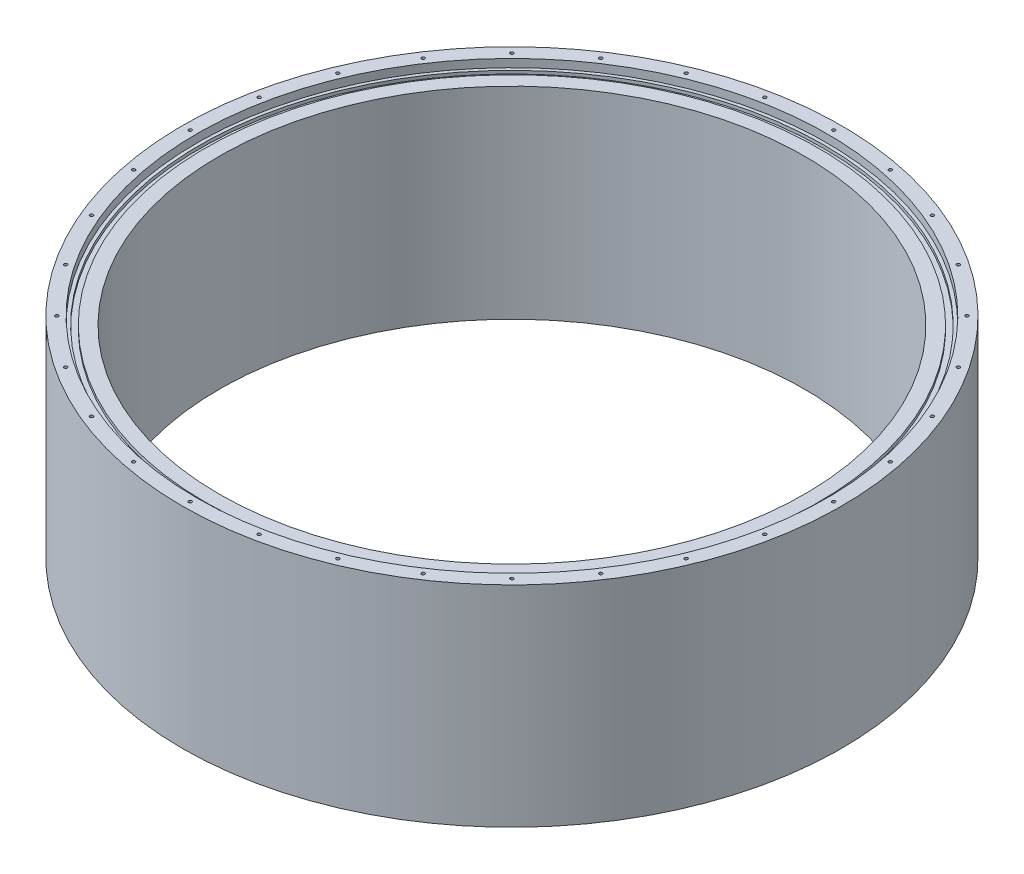
SolidWorks part; units mm, degrees
material "PVC Rigid"
ref_plane "Front" through (0, 0, 0) normal (0, 0, 1) x (1, 0, 0)
ref_plane "Top" through (0, 0, 0) normal (0, 1, 0) x (1, 0, 0)
ref_plane "Right" through (0, 0, 0) normal (1, 0, 0) x (0, 0, -1)
sketch "Sketch1" plane through (0, 0, 0) normal (0, 0, 1) x (1, 0, 0)
  line L0 (225.6, 74.685) -> (243, 74.685)
  line L1 (243, 74.685) -> (243, 80.885)
  line L2 (243, 80.885) -> (254, 80.885)
  line L3 (254, 80.885) -> (254, -80.885)
  line L4 (254, -80.885) -> (225.6, -80.885)
  line L5 (225.6, -80.885) -> (225.6, 74.685)
  line L6 (0, 80.885) -> (0, -80.885) construction
  line L7 (0, 0) -> (225.6, 0) construction
  dimension "D1" = 508
  dimension "D2" = 11
  dimension "D3" = 28.4
  dimension "D4" = 6.2
  dimension "D5" = 161.77
  dimension "D6" = 225.6
  dimension "D7" = 155.57
revolve "Revolve1" add sketch "Sketch1" angle 360 about L6
sketch "Sketch2" plane through (0, 0, 0) normal (0, 0, 1) x (1, 0, 0)
  line L0 (0, 80.885) -> (0, -80.885) construction
  line L1 (254, 80.885) -> (-254, 80.885) construction
  line L2 (-254, -80.885) -> (254, -80.885) construction
  line L3 (240.5, 72.272) -> (240.5, -77.587) construction
  line L4 (236.3344, 74.685) -> (240.5, 74.685)
  line L5 (236.3344, 74.685) -> (236.3344, 72.272)
  line L6 (236.3344, 72.272) -> (240.5, 72.272)
  line L7 (240.5, 74.685) -> (240.5, 72.272)
  line L8 (225.6, 74.685) -> (-225.6, 74.685) construction
  line L9 (225.6, 74.685) -> (-225.6, 74.685) construction
  line L10 (254, -80.885) -> (254, 80.885) construction
  line L12 (236.3344, -78.472) -> (240.5, -78.472) construction
  line L13 (236.3344, -78.472) -> (236.3344, -80.885) construction
  line L14 (236.3344, -80.885) -> (240.5, -80.885) construction
  line L15 (240.5, -78.472) -> (240.5, -80.885) construction
  dimension "D1" = 13.5
  dimension "D2" = 2.413
  dimension "D3" = 4.1656
revolve "Cut-Revolve1" cut sketch "Sketch2" angle 360 about L0
hole_wizard "M3x0.5 Tapped Hole1" positions "Sketch3" profile "Sketch4" tap size "M3x0.5" standard "ANSI Metric"
sketch "Sketch3" plane through (0, 80.885, 0) normal (0, 1, 0) x (1, 0, 0)
  point P0 (248, 0)
  dimension "D1" = 248
sketch "Sketch4" plane through (248, 80.885, 0) normal (1, 0, 0) x (0, 0, 1)
  line L0 (0, 0) -> (0, 10.2511)
  line L1 (0, 10.2511) -> (1.25, 9.5)
  line L2 (1.25, 9.5) -> (1.25, 0)
  line L5 (1.25, 0) -> (0, 0)
  line L10 (0, 10.2511) -> (-1.25, 9.5) construction
  line L11 (0, -6.35) -> (0, 107.95) construction
  dimension "Tap Drill Dia." = 2.5
  dimension "Tap Drill Depth" = 9.5
  dimension "Drill Angle" = 118
cosmetic thread "Hole Thread1" parameters "D1"=8, "D2"=3
pattern_circular "CirPattern1" count 32 over 360 about axis through (0, 0, 0) along (0, 1, 0) of "M3x0.5 Tapped Hole1"
mirror "Mirror1" about plane through (0, 0, 0) normal (0, 1, 0) of "CirPattern1", "M3x0.5 Tapped Hole1"
hole_wizard "Ø5.0mm Dowel Hole1" positions "Sketch5" profile "Sketch6" hole size "Ø5.0" standard "ANSI Metric"
sketch "Sketch5" plane through (0, -80.885, 0) normal (0, -1, 0) x (-1, 0, 0)
  line L2 (0, 0) -> (0, 204.5498) construction
  line L3 (-23.7697, 246.8583) -> (0, 0) construction
  line L4 (0, 0) -> (24.3723, -253.116) construction
  circle A0 centre (0, 0) radius 248 construction
  point P6 (-23.7697, 246.8583)
  point P8 (23.7697, -246.8583)
  point P24 (0, 0)
  dimension "D1" = 5.5
sketch "Sketch6" plane through (-23.7697, -80.885, 246.8583) normal (1, 0, 0) x (0, 0, -1)
  line L0 (0, 0) -> (0, 7.5172)
  line L1 (0, 7.5172) -> (2.525, 6)
  line L2 (2.525, 6) -> (2.525, 0)
  line L5 (2.525, 0) -> (0, 0)
  line L10 (0, 7.5172) -> (-2.525, 6) construction
  line L11 (0, -6.35) -> (0, 107.95) construction
  dimension "Hole Dia." = 5.05
  dimension "Hole Depth" = 6
  dimension "Drill Angle" = 118
